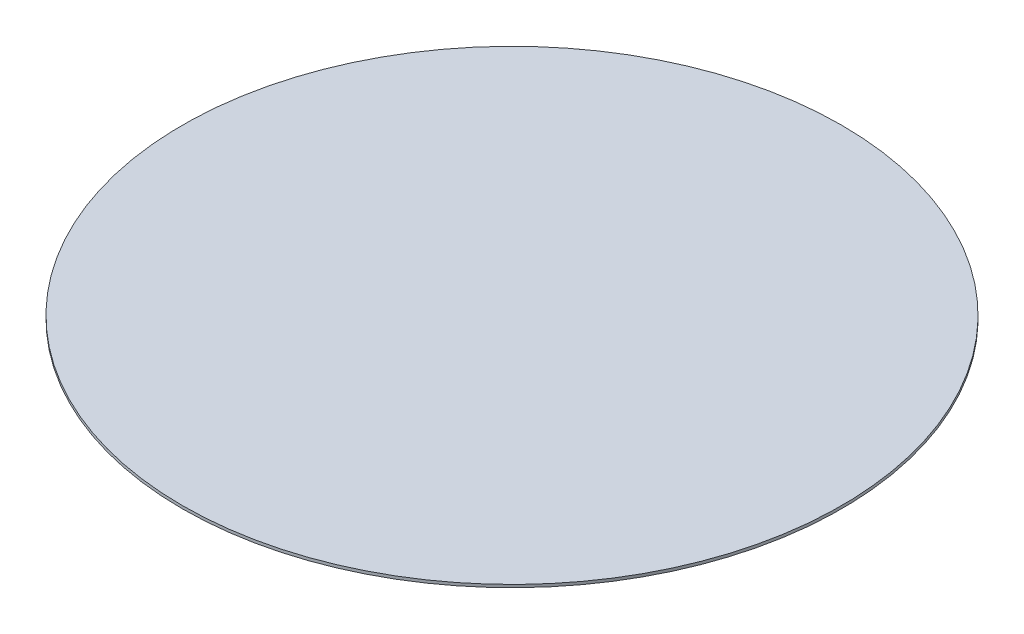
SolidWorks part; units mm, degrees
ref_plane "Front Plane" through (0, 0, 0) normal (0, 0, 1) x (1, 0, 0)
ref_plane "Top Plane" through (0, 0, 0) normal (0, 1, 0) x (1, 0, 0)
ref_plane "Right Plane" through (0, 0, 0) normal (1, 0, 0) x (0, 0, -1)
sketch "Sketch1" plane through (0, 0, 0) normal (0, 1, 0) x (1, 0, 0)
  circle A0 centre (0, 0) radius 1750
extrude "Boss-Extrude1" add sketch "Sketch1" along normal blind 15
